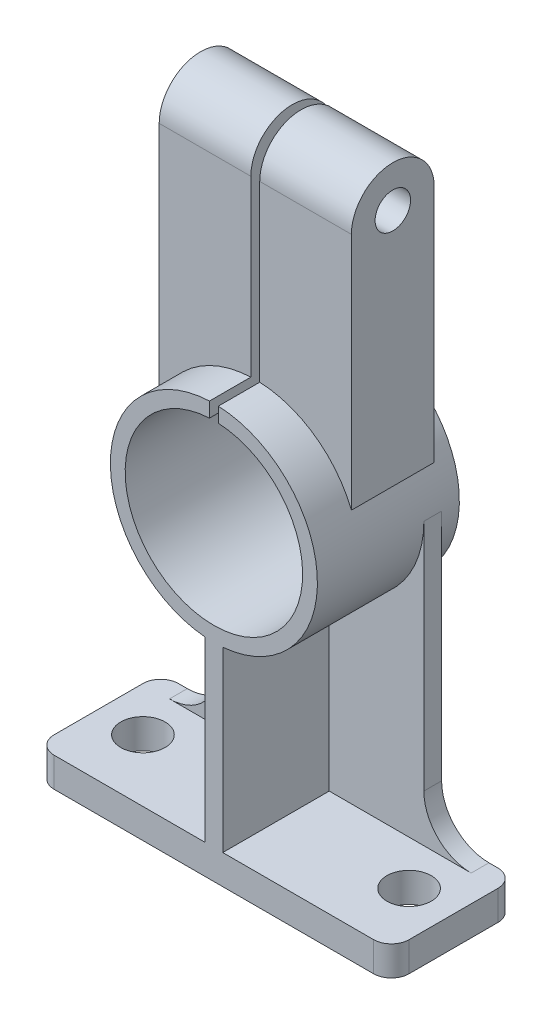
SolidWorks part; units mm, degrees
material "1060 Alloy"
ref_plane "Front Plane" through (0, 0, 0) normal (0, 0, 1) x (1, 0, 0)
ref_plane "Top Plane" through (0, 0, 0) normal (0, 1, 0) x (1, 0, 0)
ref_plane "Right Plane" through (0, 0, 0) normal (1, 0, 0) x (0, 0, -1)
sketch "Sketch1" plane through (0, 0, 0) normal (0, 1, 0) x (1, 0, 0)
  line L1 (-54, 21) -> (54, 21)
  line L2 (-60, 15) -> (-60, -15)
  line L3 (-54, -21) -> (54, -21)
  line L4 (60, 15) -> (60, -15)
  line L5 (-60, 21) -> (60, -21) construction
  line L6 (-60, -21) -> (60, 21) construction
  arc A0 (-60, -15) -> (-54, -21) centre (-54, -15) ccw
  arc A1 (-54, 21) -> (-60, 15) centre (-54, 15) ccw
  arc A2 (54, 21) -> (60, 15) centre (54, 15) cw
  arc A3 (54, -21) -> (60, -15) centre (54, -15) ccw
  circle A4 centre (-45, 0) radius 7.5
  circle A5 centre (45, 0) radius 7.5
  point P0 (0, 0)
  point P22 (0, 0)
  point P23 (-60, 0)
  dimension "D3" = 6
  dimension "D4" = 15
  dimension "D1" = 42
  dimension "D2" = 120
  dimension "D5" = 21
  dimension "D6" = 21
  dimension "D7" = 15
  dimension "D8" = 15
extrude "Boss-Extrude1" add sketch "Sketch1" along normal blind 10
sketch "Sketch2" plane through (0, 0, 21) normal (0, 0, 1) x (1, 0, 0)
  line L0 (-54, 10) -> (54, 10) construction
  circle A0 centre (0, 105) radius 30
  circle A1 centre (0, 105) radius 35
  dimension "D1" = 70
  dimension "D2" = 60
  dimension "D3" = 95
extrude "Boss-Extrude2" add sketch "Sketch2" against normal blind 48 separate body
sketch "Sketch3" plane through (0, 0, -21) normal (0, 0, -1) x (-1, 0, 0)
  line L0 (-54, 10) -> (54, 10) construction
  line L1 (-35, 10) -> (35, 10)
  line L2 (-35, 105) -> (-35, 10)
  line L3 (35, 105) -> (35, 10)
  circle A0 centre (0, 105) radius 35 construction
  arc A1 (-35, 105) -> (35, 105) centre (0, 105) ccw
extrude "Boss-Extrude3" add sketch "Sketch3" against normal blind 6
sketch "Sketch4" plane through (0, 0, 0) normal (1, 0, 0) x (0, 0, -1)
  line L2 (27, 70) -> (21, 20)
  line L3 (21, 105) -> (21, 10) construction
  line L4 (15, 0) -> (21, 0) construction
  line L5 (27, 70) -> (27, 140) construction
  line L6 (21, 70) -> (21, 20)
  line L8 (27, 73) -> (21, 73)
  line L9 (27, 73) -> (27, 70)
  line L10 (21, 73) -> (21, 70)
  dimension "D1" = 20
extrude "Boss-Extrude6" add sketch "Sketch4" along normal mid plane 6
sketch "Sketch5" plane through (0, 0, 21) normal (0, 0, 1) x (1, 0, 0)
  line L0 (0, 70) -> (0, 10)
  line L1 (-54, 10) -> (54, 10) construction
  circle A1 centre (0, 105) radius 35 construction
  point P0 (0, 0)
rib "Rib3" sketch "Sketch5" sketch "Sketch5" thickness 6 extrusion direction normal to sketch draft on no parameters "D1"=6
fillet "Fillet1" radius 16 2 edges at (35, 10, -18) (-35, 10, -18)
sketch "Sketch6" plane through (0, 0, 0) normal (1, 0, 0) x (0, 0, -1)
  line L1 (21, 70.1288) -> (21, 105) construction
  circle A0 centre (7, 198.7766) radius 14
  circle A1 centre (7, 198.7766) radius 6
  dimension "D1" = 28
  dimension "D2" = 12
  dimension "D3" = 14
extrude "Boss-Extrude7" add sketch "Sketch6" along normal mid plane 65 separate body
sketch "Sketch7" plane through (0, 0, 0) normal (1, 0, 0) x (0, 0, -1)
  line L2 (21, 198.7766) -> (21, 140)
  line L3 (-7, 198.7766) -> (-7, 140)
  line L4 (21, 135) -> (-7, 135)
  line L5 (21, 140) -> (21, 135)
  line L6 (-7, 140) -> (-7, 135)
  circle A0 centre (7, 198.7766) radius 14 construction
  arc A1 (-7, 198.7766) -> (21, 198.7766) centre (7, 198.7766) ccw
extrude "Boss-Extrude8" add sketch "Sketch7" along normal mid plane 65
sketch "Sketch8" plane through (0, 135, 0) normal (0, -1, 0) x (1, 0, 0)
  line L4 (18.0278, 7) -> (18.0278, -21)
  line L5 (18.0278, -21) -> (32.5, -21)
  line L6 (32.5, -21) -> (32.5, 7)
  line L7 (32.5, 7) -> (18.0278, 7)
  line L8 (18.0278, 7) -> (18.0278, -21)
  line L9 (18.0278, -21) -> (32.5, -21)
  line L10 (32.5, -21) -> (32.5, 7)
  line L11 (32.5, 7) -> (18.0278, 7)
  dimension "D1" = 0
extrude "Boss-Extrude9" add sketch "Sketch8" along normal up to next
sketch "Sketch9" plane through (0, 135, 0) normal (0, -1, 0) x (1, 0, 0)
  line L4 (-18.0278, -21) -> (-18.0278, 7)
  line L5 (-18.0278, 7) -> (-32.5, 7)
  line L6 (-32.5, 7) -> (-32.5, -21)
  line L7 (-32.5, -21) -> (-18.0278, -21)
  line L8 (-18.0278, -21) -> (-18.0278, 7)
  line L9 (-18.0278, 7) -> (-32.5, 7)
  line L10 (-32.5, 7) -> (-32.5, -21)
  line L11 (-32.5, -21) -> (-18.0278, -21)
  dimension "D1" = 0
extrude "Boss-Extrude10" add sketch "Sketch9" along normal up to next
sketch "Sketch10" plane through (0, 0, 0) normal (0, 0, 1) x (1, 0, 0)
  line L0 (0, 212.7766) -> (0, 105) construction
  line L1 (-1.5, 231.8815) -> (1.5, 231.8815)
  line L2 (-1.5, 231.8815) -> (-1.5, 109.2875)
  line L3 (-1.5, 109.2875) -> (1.5, 109.2875)
  line L4 (1.5, 231.8815) -> (1.5, 109.2875)
  line L5 (-1.5, 231.8815) -> (1.5, 109.2875) construction
  line L6 (-1.5, 109.2875) -> (1.5, 231.8815) construction
  line L7 (32.5, 212.7766) -> (-32.5, 212.7766) construction
  point P0 (0, 170.5845)
  point P10 (0, 109.2875)
  dimension "D1" = 3
extrude "Cut-Extrude1" cut sketch "Sketch10" against normal mid plane 65 contours L2 L3 L4 L1
